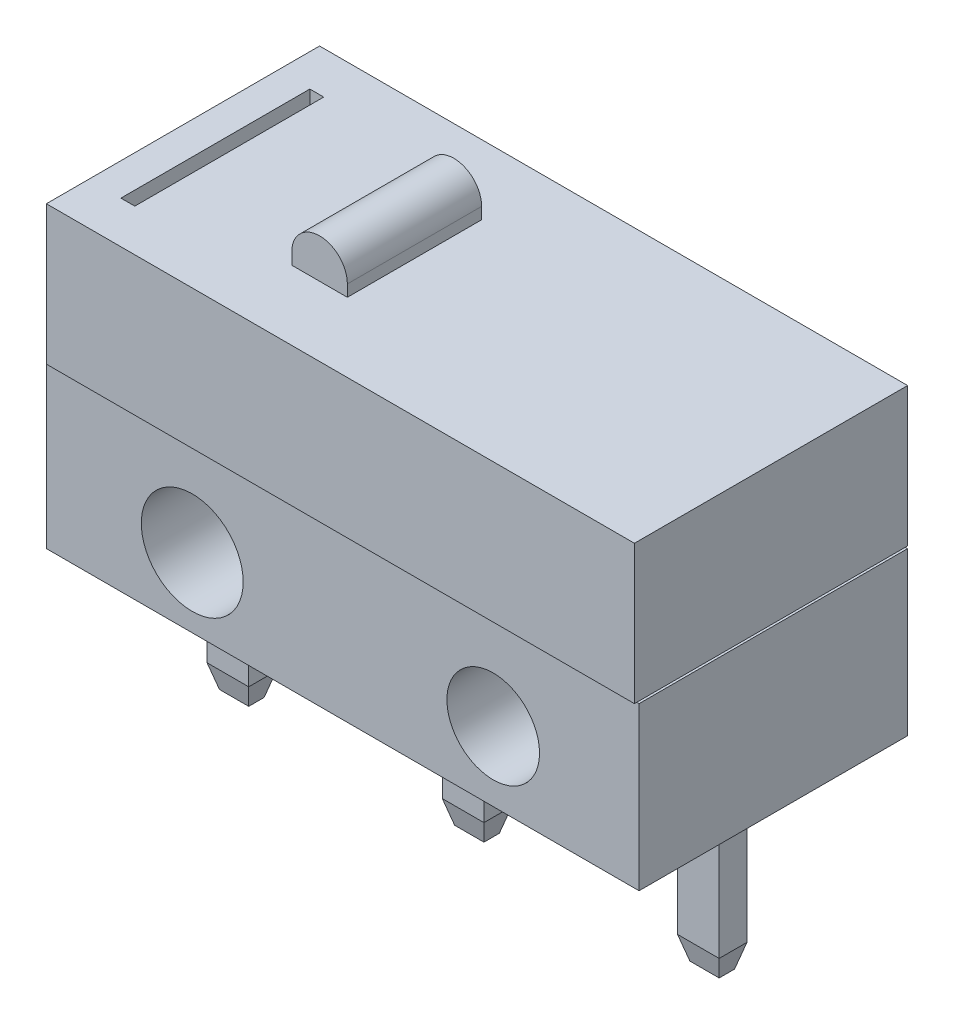
SolidWorks part; units mm, degrees
ref_plane "Front Plane" through (0, 0, 0) normal (0, 0, 1) x (1, 0, 0)
ref_plane "Top Plane" through (0, 0, 0) normal (0, 1, 0) x (1, 0, 0)
ref_plane "Right Plane" through (0, 0, 0) normal (1, 0, 0) x (0, 0, -1)
sketch "Sketch1" plane through (0, 0, 0) normal (0, 1, 0) x (1, 0, 0)
  line L1 (-6.4, -2.9) -> (6.4, -2.9)
  line L2 (-6.4, -2.9) -> (-6.4, 2.9)
  line L3 (-6.4, 2.9) -> (6.4, 2.9)
  line L4 (6.4, -2.9) -> (6.4, 2.9)
  line L5 (-6.4, -2.9) -> (6.4, 2.9) construction
  line L6 (-6.4, 2.9) -> (6.4, -2.9) construction
  point P0 (0, 0)
  dimension "D1" = 5.8
  dimension "D2" = 12.8
extrude "Boss-Extrude1" add sketch "Sketch1" along normal blind 3.5
sketch "Sketch2" plane through (0, 0, 0) normal (0, -1, 0) x (1, 0, 0)
  line L0 (-6.4, 0) -> (6.4, 0) construction
  line L1 (-6.4, -2.9) -> (-6.4, 2.9) construction
  line L2 (6.4, 2.9) -> (6.4, -2.9) construction
  line L3 (0, 2.9) -> (0, -2.9) construction
  line L4 (-6.4, 2.9) -> (6.4, 2.9) construction
  line L5 (6.4, -2.9) -> (-6.4, -2.9) construction
  line L6 (5.53, -0.3) -> (4.63, 0.3) construction
  line L7 (-0.45, -0.3) -> (0.45, -0.3)
  line L8 (-0.45, -0.3) -> (-0.45, 0.3)
  line L9 (-0.45, 0.3) -> (0.45, 0.3)
  line L10 (0.45, -0.3) -> (0.45, 0.3)
  line L11 (-0.45, -0.3) -> (0.45, 0.3) construction
  line L12 (-0.45, 0.3) -> (0.45, -0.3) construction
  line L13 (-5.53, -0.3) -> (-4.63, -0.3)
  line L14 (-5.53, -0.3) -> (-5.53, 0.3)
  line L15 (-5.53, 0.3) -> (-4.63, 0.3)
  line L16 (-4.63, -0.3) -> (-4.63, 0.3)
  line L17 (-5.53, -0.3) -> (-4.63, 0.3) construction
  line L18 (-5.53, 0.3) -> (-4.63, -0.3) construction
  line L19 (5.53, 0.3) -> (4.63, -0.3) construction
  line L20 (5.53, 0.3) -> (4.63, 0.3)
  line L21 (4.63, -0.3) -> (4.63, 0.3)
  line L22 (5.53, -0.3) -> (4.63, -0.3)
  line L23 (5.53, -0.3) -> (5.53, 0.3)
  point P12 (0, 0)
  point P18 (-5.08, 0)
  dimension "D1" = 0.6
  dimension "D2" = 0.9
  dimension "D3" = 5.08
extrude "Boss-Extrude3" add sketch "Sketch2" along normal blind 3.5
chamfer "Chamfer1" distance 0.5 angle 15 12 edges at (5.08, -3.5, -0.3) (4.63, -3.5, 0) (5.08, -3.5, 0.3) (5.53, -3.5, 0) (0, -3.5, -0.3) (-0.45, -3.5, 0) (0, -3.5, 0.3) (0.45, -3.5, 0) (-5.08, -3.5, -0.3) (-5.53, -3.5, 0) (-5.08, -3.5, 0.3) (-4.63, -3.5, 0)
sketch "Sketch3" plane through (0, 0, 2.9) normal (0, 0, 1) x (1, 0, 0)
  line L0 (0, 3.5) -> (0, 0) construction
  line L1 (-6.4, 3.5) -> (6.4, 3.5) construction
  line L2 (-6.4, 1.5) -> (6.4, 1.5) construction
  line L3 (-6.4, 3.5) -> (-6.4, 0) construction
  line L4 (6.4, 3.5) -> (6.4, 0) construction
  circle A0 centre (-3.25, 1.5) radius 1.1
  circle A1 centre (3.25, 1.5) radius 1
  dimension "D2" = 2.2
  dimension "D3" = 2
  dimension "D1" = 1.5
  dimension "D4" = 3.15
  dimension "D5" = 3.15
  dimension "D6" = 6.5
extrude "Cut-Extrude1" cut sketch "Sketch3" against normal up to surface (5.8 mm away) up to face at (0, 1.75, -2.9)
sketch "Sketch4" plane through (0, 3.5, 0) normal (0, 1, 0) x (1, 0, 0)
  line L1 (6.35, -2.95) -> (-6.35, -2.95)
  line L2 (6.35, -2.95) -> (6.35, 2.95)
  line L3 (6.35, 2.95) -> (-6.35, 2.95)
  line L4 (-6.35, -2.95) -> (-6.35, 2.95)
  line L5 (6.35, -2.95) -> (-6.35, 2.95) construction
  line L6 (6.35, 2.95) -> (-6.35, -2.95) construction
  point P0 (0, 0)
  dimension "D1" = 5.9
  dimension "D2" = 12.7
extrude "Boss-Extrude4" add sketch "Sketch4" along normal blind 3
sketch "Sketch5" plane through (0, 0, 0) normal (0, 0, 1) x (1, 0, 0)
  line L0 (-1.95, 6.5) -> (-1.95, 7.35) construction
  line L1 (-6.35, 6.5) -> (6.35, 6.5) construction
  line L2 (-2.55, 6.5) -> (-2.55, 6.75)
  line L3 (-1.35, 6.5) -> (-1.35, 6.75)
  line L4 (-2.55, 6.5) -> (-1.35, 6.5)
  circle A1 centre (3.25, 1.5) radius 1 construction
  circle A2 centre (3.25, 1.5) radius 1 construction
  arc A3 (-2.55, 6.75) -> (-1.35, 6.75) centre (-1.95, 6.75) cw
  dimension "D1" = 5.2
  dimension "D2" = 1.2
  dimension "D3" = 0.85
extrude "Boss-Extrude5" add sketch "Sketch5" along normal blind 1.45 and the other way blind 1.45
sketch "Sketch6" plane through (0, 6.5, 0) normal (0, 1, 0) x (1, 0, 0)
  line L0 (-6.35, 0) -> (6.35, 0) construction
  line L3 (-6.35, 2.95) -> (-6.35, -2.95) construction
  line L4 (6.35, -2.95) -> (6.35, 2.95) construction
  line L6 (-5.35, -2.04) -> (-5.65, -2.04)
  line L7 (-5.35, -2.04) -> (-5.35, 2.04)
  line L8 (-5.35, 2.04) -> (-5.65, 2.04)
  line L9 (-5.65, -2.04) -> (-5.65, 2.04)
  line L10 (-5.35, -2.04) -> (-5.65, 2.04) construction
  line L11 (-5.35, 2.04) -> (-5.65, -2.04) construction
  point P6 (-5.5, 0)
  dimension "D1" = 0.7
  dimension "D2" = 4.08
  dimension "D3" = 0.3
extrude "Cut-Extrude2" cut sketch "Sketch6" against normal blind 0.4
